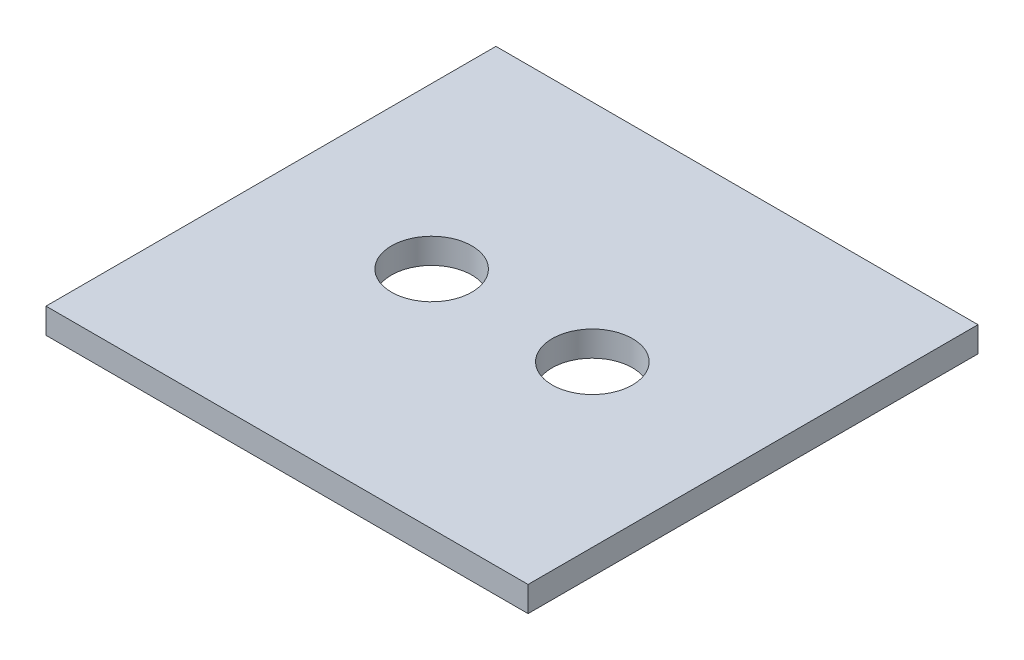
SolidWorks part; units mm, degrees
ref_plane "Front Plane" through (0, 0, 0) normal (0, 0, 1) x (1, 0, 0)
ref_plane "Top Plane" through (0, 0, 0) normal (0, 1, 0) x (1, 0, 0)
ref_plane "Right Plane" through (0, 0, 0) normal (1, 0, 0) x (0, 0, -1)
sketch "Sketch1" plane through (0, 0, 0) normal (0, 1, 0) x (1, 0, 0)
  line L0 (-6.35, 0) -> (6.35, 0) construction
  line L1 (-19.05, -17.78) -> (19.05, -17.78)
  line L2 (-19.05, -17.78) -> (-19.05, 17.78)
  line L3 (-19.05, 17.78) -> (19.05, 17.78)
  line L4 (19.05, -17.78) -> (19.05, 17.78)
  line L5 (-19.05, -17.78) -> (19.05, 17.78) construction
  line L6 (-19.05, 17.78) -> (19.05, -17.78) construction
  circle A0 centre (-6.35, 0) radius 3.175
  circle A1 centre (6.35, 0) radius 3.175
  point P0 (0, 0)
  point P8 (0, 0)
  dimension "D4" = 6.35
  dimension "D5" = 6.35
  dimension "D1" = 35.56
  dimension "D2" = 38.1
  dimension "D3" = 12.7
extrude "Boss-Extrude1" add sketch "Sketch1" along normal blind 2
